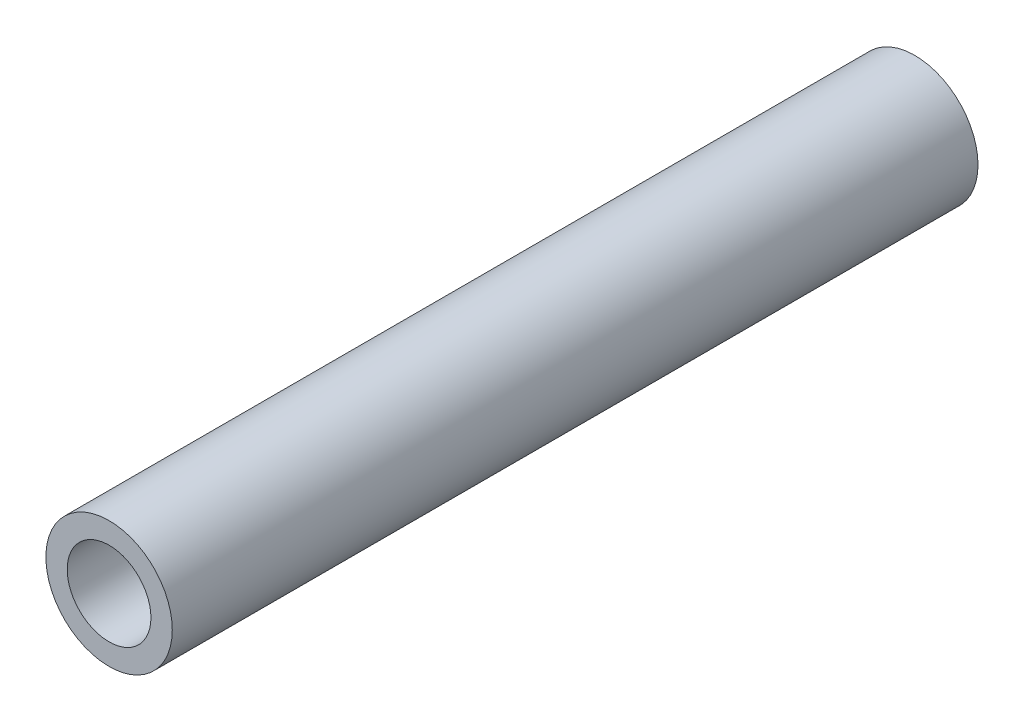
SolidWorks part; units mm, degrees
material "2014 Alloy"
ref_plane "Front Plane" through (0, 0, 0) normal (0, 0, 1) x (1, 0, 0)
ref_plane "Top Plane" through (0, 0, 0) normal (0, 1, 0) x (1, 0, 0)
ref_plane "Right Plane" through (0, 0, 0) normal (1, 0, 0) x (0, 0, -1)
sketch "Sketch1" plane through (0, 0, 0) normal (0, 0, 1) x (1, 0, 0)
  circle A0 centre (0, 0) radius 4
  circle A1 centre (0, 0) radius 2.65
  dimension "OD" = 8
  dimension "ID" = 5.3
extrude "Extrude1" add sketch "Sketch1" along normal mid plane 51
sketch "Sketch2" plane through (0, 0, 0) normal (1, 0, 0) x (0, 0, -1)
  line L0 (-25.5, -2.65) -> (25.5, -2.65) construction
  line L3 (25.5, 2.65) -> (-25.5, 2.65) construction
  line L5 (-25.5, -2.65) -> (25.5, -2.65)
  line L6 (25.5, 2.65) -> (-25.5, 2.65)
sketch "Sketch4" plane through (0, 0, 25.5) normal (0, 0, 1) x (1, 0, 0)
  line L0 (0, 0) -> (-1.8738, 1.8738)
  line L1 (0, -4.4) -> (0, 4.4) construction
  circle A0 centre (0, 0) radius 2.65 construction
  dimension "D1" = 45
